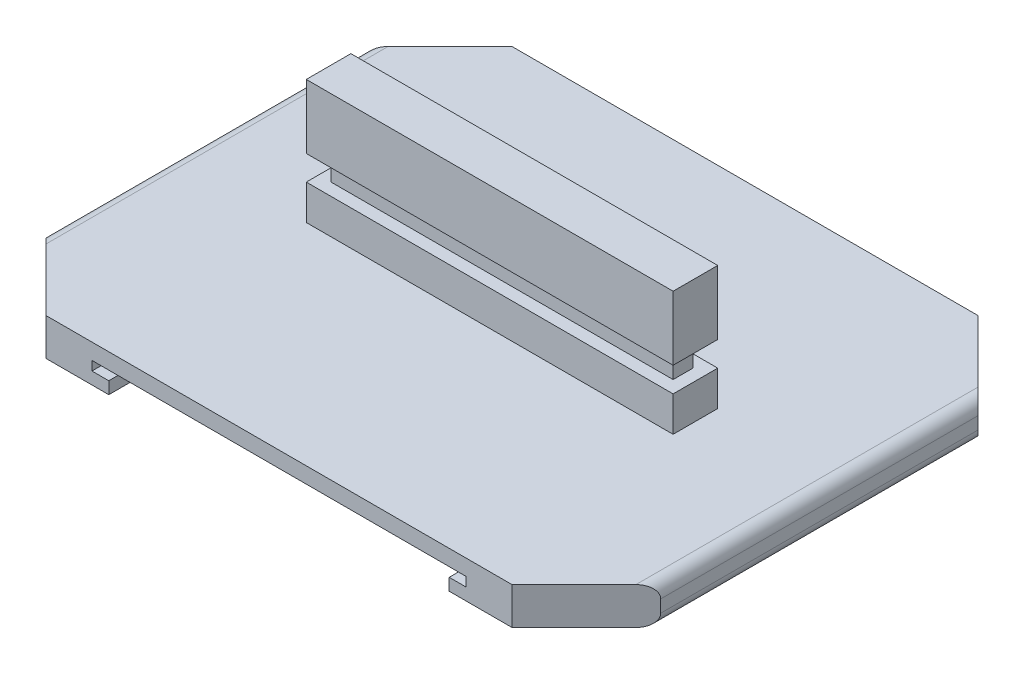
SolidWorks part; units mm, degrees
ref_plane "前视基准面" through (0, 0, 0) normal (0, 0, 1) x (1, 0, 0)
ref_plane "上视基准面" through (0, 0, 0) normal (0, 1, 0) x (1, 0, 0)
ref_plane "右视基准面" through (0, 0, 0) normal (1, 0, 0) x (0, 0, -1)
other "Configuration Table"
sketch "草图1" plane through (0, 0, 0) normal (0, 1, 0) x (1, 0, 0)
  line L0 (-12.4, 6.4) -> (-9.4, 9.4)
  line L1 (-9.4, -9.4) -> (9.4, -9.4)
  line L2 (-12.4, -6.4) -> (-12.4, 6.4)
  line L3 (-9.4, 9.4) -> (9.4, 9.4)
  line L4 (12.4, -6.4) -> (12.4, 6.4)
  line L5 (-12.4, -9.4) -> (12.4, 9.4) construction
  line L6 (-12.4, 9.4) -> (12.4, -9.4) construction
  line L7 (9.4, 9.4) -> (12.4, 6.4)
  line L8 (9.4, -9.4) -> (12.4, -6.4)
  line L9 (-12.4, -6.4) -> (-9.4, -9.4)
  point P0 (0, 0)
  dimension "D1" = 24.8
  dimension "D2" = 18.8
extrude "凸台-拉伸1" add sketch "草图1" along normal blind 1.5
sketch "草图2" plane through (0, 1.5, 0) normal (0, 1, 0) x (1, 0, 0)
  line L1 (-7.4, -0.9) -> (7.4, -0.9)
  line L2 (-7.4, -0.9) -> (-7.4, 0.9)
  line L3 (-7.4, 0.9) -> (7.4, 0.9)
  line L4 (7.4, -0.9) -> (7.4, 0.9)
  line L5 (-7.4, -0.9) -> (7.4, 0.9) construction
  line L6 (-7.4, 0.9) -> (7.4, -0.9) construction
  point P0 (0, 0)
  dimension "D1" = 14.8
  dimension "D2" = 1.8
extrude "凸台-拉伸2" add sketch "草图2" along normal blind 5
sketch "草图5" plane through (0, 0, 0.9) normal (0, 0, 1) x (1, 0, 0)
  line L0 (-7.4, 6.5) -> (-7.4, 1.5) construction
  line L1 (-7.6395, 3.4126) -> (-7.1605, 3.4126)
  line L2 (-7.6395, 3.4126) -> (-7.6395, 3.54)
  line L3 (-7.6395, 3.54) -> (-7.1605, 3.54)
  line L4 (-7.1605, 3.4126) -> (-7.1605, 3.54)
  line L5 (-7.6395, 3.4126) -> (-7.1605, 3.54) construction
  line L6 (-7.6395, 3.54) -> (-7.1605, 3.4126) construction
  point P0 (-7.4, 3.4763)
extrude "切除-拉伸1" cut sketch "草图5" against normal blind 0.1
sketch "草图4" plane through (0, 3.4126, 0) normal (0, 1, 0) x (1, 0, 0)
  line L9 (-6.9, -0.4) -> (6.9, -0.4)
  line L10 (-6.9, -0.4) -> (-6.9, 0.4)
  line L11 (-7.8149, -1.2858) -> (7.8149, -1.2858)
  line L12 (-7.8149, -1.2858) -> (-7.8149, 1.2858)
  line L13 (-7.8149, 1.2858) -> (7.8149, 1.2858)
  line L14 (7.8149, -1.2858) -> (7.8149, 1.2858)
  line L15 (-6.9, 0.4) -> (6.9, 0.4)
  line L16 (6.9, -0.4) -> (6.9, 0.4)
  line L17 (-6.9, -0.4) -> (6.9, 0.4) construction
  line L18 (-6.9, 0.4) -> (6.9, -0.4) construction
  point P0 (0, 0)
  point P1 (0, 0)
  point P5 (0, 0)
  point P7 (0, 0)
  point P8 (0, 0)
extrude "切除-拉伸2" cut sketch "草图4" along normal blind 0.5 and the other way blind 0.5
sketch "草图6" plane through (0, 0, 9.4) normal (0, 0, 1) x (1, 0, 0)
  line L0 (-7.5471, 0) -> (7.5471, 0)
  line L1 (-7.5471, 0.8592) -> (7.5471, 0.8592)
  line L2 (-7.5471, 0.8592) -> (-7.5471, 0)
  line L4 (7.5471, 0.8592) -> (7.5471, 0)
  line L5 (-6.867, 0) -> (-6.867, 0.4881)
  line L6 (-6.867, 0.4881) -> (-7.5471, 0.4881)
  line L7 (0, 0) -> (0, 0.8592)
  line L8 (6.867, 0) -> (6.867, 0.4881)
  line L9 (6.867, 0.4881) -> (7.5471, 0.4881)
  point P0 (0, 0)
  line M12 (-9.4, 0) -> (9.4, 0)
extrude "切除-拉伸3" cut sketch "草图6" against normal blind 117.5 contours L0 L7 L1 L2 L6 L5 | L8 L9 L4 L1 L7 M12
sketch "草图9" plane through (0, 0, 9.4) normal (0, 0, 1) x (1, 0, 0)
  line L0 (9.4, 1.5) -> (12.4, 1.5) construction
  line L1 (-11.9, 0) -> (11.9, 0)
  line L2 (-12.4, 0.5) -> (-12.4, 1)
  line L3 (-11.9, 1.5) -> (11.9, 1.5)
  line L4 (12.4, 0.5) -> (12.4, 1)
  line L5 (12.4, 1.5) -> (12.4, 0) construction
  line L6 (-11.9, 1.5) -> (-13.6592, 1.5)
  line L7 (-13.6592, -1.6319) -> (14.4564, -1.6319)
  line L8 (-13.6592, -1.6319) -> (-13.6592, 1.5)
  line L10 (14.4564, -1.6319) -> (14.4564, 1.5)
  line L11 (11.9, 1.5) -> (14.4564, 1.5)
  arc A0 (11.9, 1.5) -> (12.4, 1) centre (11.9, 1) cw
  arc A1 (12.4, 0.5) -> (11.9, 0) centre (11.9, 0.5) cw
  arc A2 (-12.4, 0.5) -> (-11.9, 0) centre (-11.9, 0.5) ccw
  arc A3 (-12.4, 1) -> (-11.9, 1.5) centre (-11.9, 1) cw
  point P11 (12.4, 1.5)
  point P16 (-12.4, 0)
  line M12 (6.867, 0) -> (9.4, 0)
  line M16 (-9.4, 0) -> (-6.867, 0)
  dimension "D1" = 0.5
extrude "切除-拉伸4" cut sketch "草图9" against normal blind 19.5 contours L2 A3 L6 L8 L7 L10 L11 A0 L4 A1 L1 A2 M12 M16
